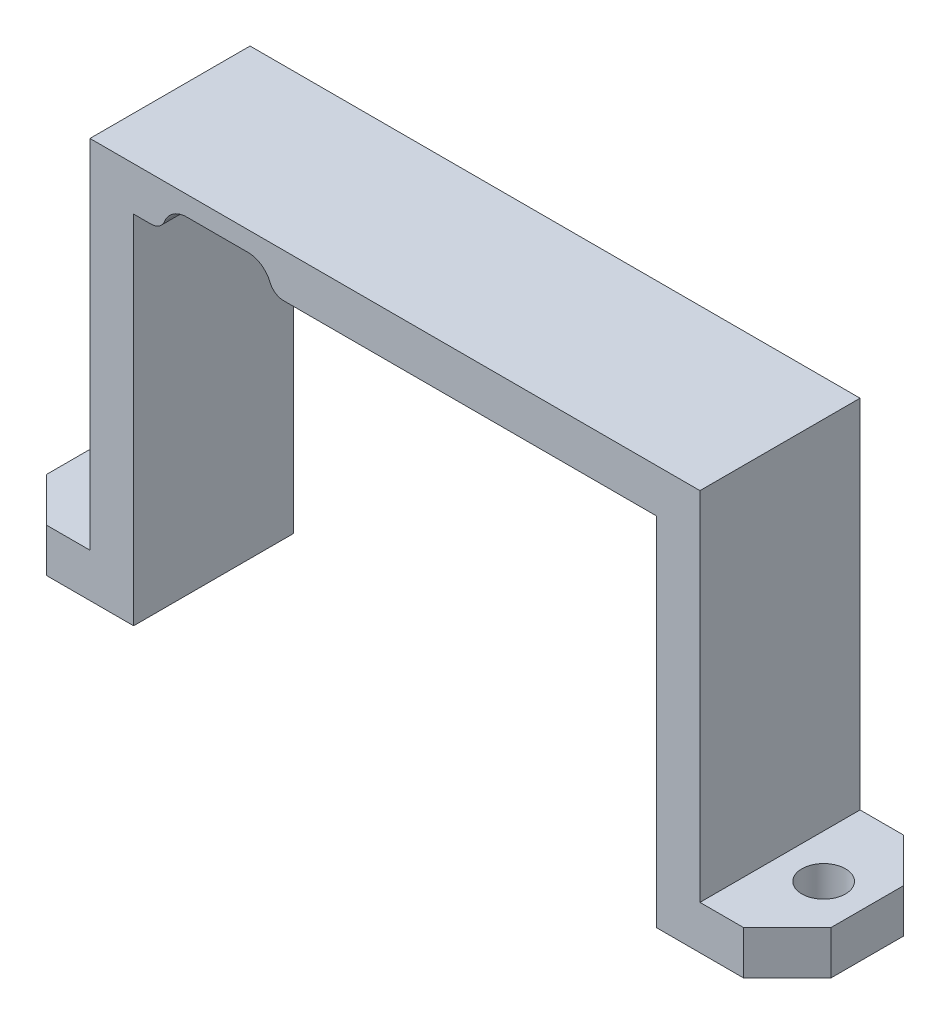
SolidWorks part; units mm, degrees
ref_plane "Front Plane" through (0, 0, 0) normal (0, 0, 1) x (1, 0, 0)
ref_plane "Top Plane" through (0, 0, 0) normal (0, 1, 0) x (1, 0, 0)
ref_plane "Right Plane" through (0, 0, 0) normal (1, 0, 0) x (0, 0, -1)
sketch "Sketch1" plane through (0, 0, 0) normal (0, 0, 1) x (1, 0, 0)
  line L0 (-26.955, 0) -> (-17.955, 0)
  line L1 (-17.955, 0) -> (-17.955, 24.5)
  line L2 (-17.955, 24.5) -> (17.955, 24.5)
  line L3 (0, 24.5) -> (0, 39.5072) construction
  line L4 (20.955, 27.5) -> (-20.955, 27.5)
  line L5 (-20.955, 27.5) -> (-20.955, 3)
  line L6 (-20.955, 3) -> (-26.955, 3)
  line L7 (-26.955, 3) -> (-26.955, 0)
  line L8 (26.955, 3) -> (26.955, 0)
  line L9 (20.955, 3) -> (26.955, 3)
  line L10 (20.955, 27.5) -> (20.955, 3)
  line L11 (17.955, 0) -> (17.955, 24.5)
  line L12 (26.955, 0) -> (17.955, 0)
  point P12 (0, 27.5)
  dimension "D1" = 24.5
  dimension "D2" = 3
  dimension "D3" = 3
  dimension "D4" = 17.955
  dimension "D5" = 6
  dimension "D6" = 3
extrude "Boss-Extrude1" add sketch "Sketch1" along normal blind 11
chamfer "Chamfer1" distance 3 angle 45 4 edges at (26.955, 1.5, 0) (26.955, 1.5, 11) (-26.955, 1.5, 0) (-26.955, 1.5, 11)
sketch "Sketch2" plane through (0, 3, 0) normal (0, 1, 0) x (1, 0, 0)
  line L0 (-26.955, -8) -> (-26.955, -3) construction
  line L2 (0, -6.05) -> (0, 6.05) construction
  circle A0 centre (-23.955, -5.5) radius 1.5
  circle A1 centre (23.955, -5.5) radius 1.5
  dimension "D2" = 3
  dimension "D1" = 3
extrude "Cut-Extrude1" cut sketch "Sketch2" against normal through all
sketch "Sketch3" plane through (0, 0, 11) normal (0, 0, 1) x (1, 0, 0)
  line L0 (-14.305, 24.5) -> (-10.105, 24.5) construction
  line L2 (-14.305, 26.15) -> (-10.105, 26.15)
  line L3 (-14.305, 22.85) -> (-10.105, 22.85)
  line L4 (-17.955, 24.5) -> (17.955, 24.5) construction
  arc A0 (-14.305, 26.15) -> (-14.305, 22.85) centre (-14.305, 24.5) ccw
  arc A1 (-10.105, 22.85) -> (-10.105, 26.15) centre (-10.105, 24.5) ccw
  point P2 (0, 0)
  point P4 (-12.205, 24.5)
  point P9 (-15.955, 24.5)
  point P10 (-8.455, 24.5)
  point P13 (0, 0)
  point P14 (0, 0)
  dimension "D1" = 3.3
  dimension "D2" = 2
  dimension "D3" = 7.5
extrude "Cut-Extrude2" cut sketch "Sketch3" against normal through all
fillet "Fillet1" radius 1 2 edges at (-8.455, 24.5, 5.5) (-15.955, 24.5, 5.5)
